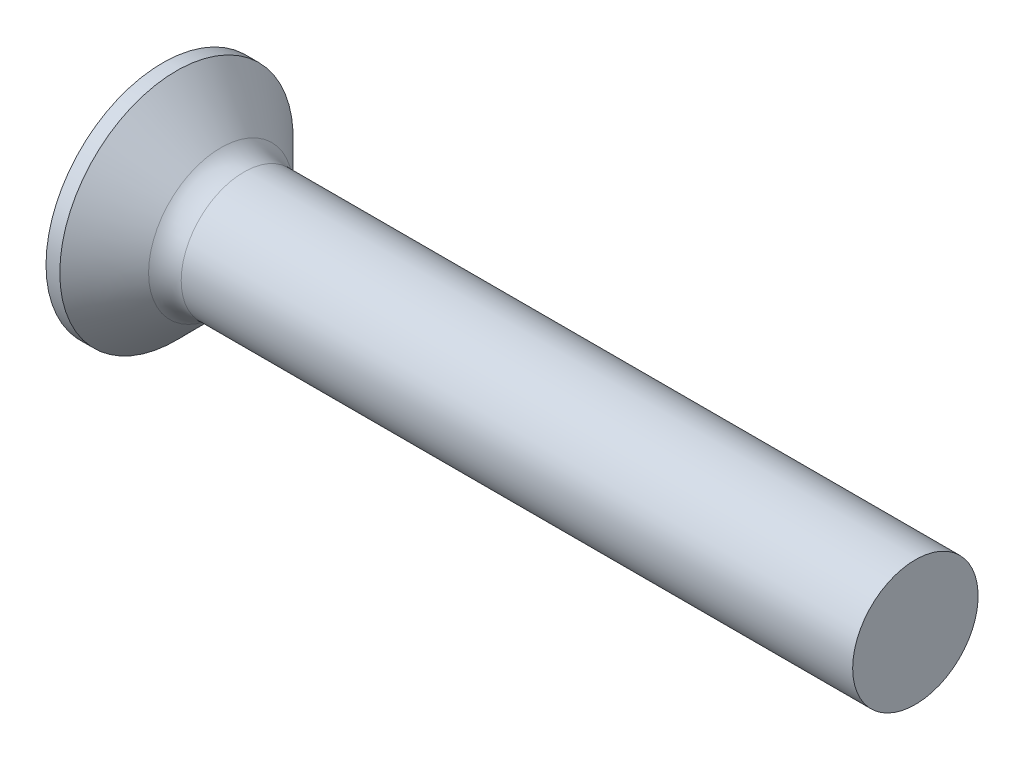
SolidWorks part; units mm, degrees
revolve "Base-Revolve" add sketch "BodySke"
sketch "BodySke" plane through (0, 0, 0) normal (0, 0, 1) x (1, 0, 0)
  line L0 (0, 0) -> (0, 4.65)
  line L1 (0, 4.65) -> (0.55, 4.65)
  line L2 (2.7, 2.5) -> (30, 2.5)
  line L3 (30, 2.5) -> (30, 0)
  line L4 (30, 0) -> (0, 0)
  line L5 (-6.35, 0) -> (82.55, 0) construction
  line L6 (2.7, -2.5) -> (30, -2.5) construction
  line L7 (0.55, -4.65) -> (2.7, -2.5) construction
  line L8 (0.55, 4.65) -> (2.7, 2.5)
  line L9 (0, -4.65) -> (0.55, -4.65) construction
  line L10 (3.5, 4.0875) -> (3.5, -5.4375) construction
  line L11 (0, 6.35) -> (0, -3.175) construction
  dimension "Diameter" = 5
  dimension "Head_ht" = 2.7
  dimension "Head_dia" = 9.3
  dimension "Head_ang" = 90
  dimension "D6" = 0.55
  dimension "Advance" = 0.8
cosmetic thread "ThreadCosmetic" [suppressed]
fillet "Fillet1" radius 1.3 1 edges at (2.7, 0, 2.5)
ref_plane "Plane1" through (0, 0, 0) normal (0, 0, 1) x (1, 0, 0)
ref_plane "Plane2" through (0, 0, 0) normal (0, 1, 0) x (1, 0, 0)
ref_plane "Plane3" through (0, 0, 0) normal (1, 0, 0) x (0, 0, -1)
sketch "Sketch3" plane through (0, 0, 0) normal (-1, 0, 0) x (0, 0, 1)
  line L0 (-0.515, 2.45) -> (0.515, 2.45)
  line L1 (0.515, 2.45) -> (0.515, -2.45)
  line L2 (0.515, -2.45) -> (-0.515, -2.45)
  line L3 (-0.515, -2.45) -> (-0.515, 2.45)
  dimension "Cross_dia" = 4.9
  dimension "Cross_width" = 1.03
  dimension "D1" = 2.45
  dimension "D2" = 0.515
ref_plane "Plane4" through (3.05, 0, 0) normal (-1, 0, 0) x (0, 0, 1)
sketch "Sketch4" plane through (3.05, 0, 0) normal (-1, 0, 0) x (0, 0, 1)
  line L0 (-0.515, 0.9293) -> (0.515, 0.9293)
  line L3 (0.515, 0.9293) -> (0.515, -0.9293)
  line L4 (0.515, -0.9293) -> (-0.515, -0.9293)
  line L5 (-0.515, -0.9293) -> (-0.515, 0.9293)
  dimension "D2" = 1.8587
  dimension "D1" = 1.03
  dimension "D4" = 0.9293
  dimension "D3" = 0.515
loft "Recess" cut profiles "Sketch3", "Sketch4"
pattern_circular "RecPat" count 2 every 90 about axis through (0, 0, 0) along (1, 0, 0) of "Recess"
sketch "RecCorSke" plane through (0, 0, 0) normal (0, 0, 1) x (1, 0, 0)
  line L0 (-3.175, 0) -> (15.875, 0) construction
  line L2 (0, 0) -> (0, 1.0643)
  line L3 (0, 1.0643) -> (3.05, 0.851)
  line L4 (3.05, 0.851) -> (3.3265, 0)
  line L5 (3.3265, 0) -> (0, 0)
  dimension "Diameter" = 1.702
  dimension "Depth" = 3.05
  dimension "Draft_angle" = 4
  dimension "Bottom_angle" = 18
revolve "RecessCore" cut sketch "RecCorSke" angle 360 about L0
sketch "ThdSchSke" plane through (0, 0, 0) normal (0, 0, 1) x (1, 0, 0)
  line L0 (3.5, -2.055) -> (3.1884, -2.5)
  line L1 (3.5, -2.055) -> (3.8116, -2.5)
  line L2 (3.8116, -2.5) -> (3.8116, -3.125)
  line L3 (-3.175, 0) -> (5.1513, 0) construction
  line L5 (3.8116, -3.125) -> (3.1884, -3.125)
  line L6 (3.1884, -3.125) -> (3.1884, -2.5)
  line L7 (0, 4.65) -> (0, -4.65) construction
  dimension "Diameter" = 5
  dimension "Thread_minor" = 4.11
  dimension "Start" = 3.5
revolve "ThreadSchematic" [suppressed] cut sketch "ThdSchSke" angle 360 about L3
pattern_linear "ThdSchPat" [suppressed]
equation "\"D1@Sketch3\" = \"Cross_dia@Sketch3\" / 2"
equation "\"D2@Sketch3\" = \"Cross_width@Sketch3\" / 2"
equation "\"Depth@RecCorSke\" = \"Cross_depth@Plane4\""
equation "\"D1@Sketch4\" = \"Cross_width@Sketch3\""
equation "\"D2@Sketch4\" = \"Cross_dia@Sketch3\" - 2.0 * \"Cross_depth@Plane4\" * tan(26.5  * 0.017453292)"
equation "\"D3@Sketch4\" = \"D1@Sketch4\" / 2"
equation "\"D4@Sketch4\" = \"D2@Sketch4\" / 2"
equation "\"Thread_length@ThreadCosmetic\" = ((sgn( (\"Length@BodySke\" - \"Advance@BodySke\" * 1.0 - \"Head_ht@BodySke\" ) - \"Thread_nom@BodySke\" )-1)*( (\"Length@BodySke\" - \"Advance@BodySke\" * 1.0 - \"Head_ht@BodySke\" ) - \"Thread_nom@BodySke\" ))/-2+ \"Thread_nom@BodySke\""
equation "\"Thread_minor@ThdSchSke\" = \"Thread_minor@ThreadCosmetic\""
equation "\"Diameter@ThdSchSke\" = \"Diameter@BodySke\""
equation "\"Overcut@ThdSchSke\" = \"Diameter@BodySke\" * 1.25"
equation "\"Start@ThdSchSke\" = 0.000001 + \"Length@BodySke\" - \"Thread_length@ThreadCosmetic\"  '---Countersunk---"
equation "\"Num_threads@ThdSchPat\" = int( \"Thread_length@ThreadCosmetic\" / \"Advance@BodySke\" + 0.999 )  + 1"
equation "\"Advance@ThdSchPat\" = \"Thread_length@ThreadCosmetic\" /  (\"Num_threads@ThdSchPat\" - 1) 'relax it"
